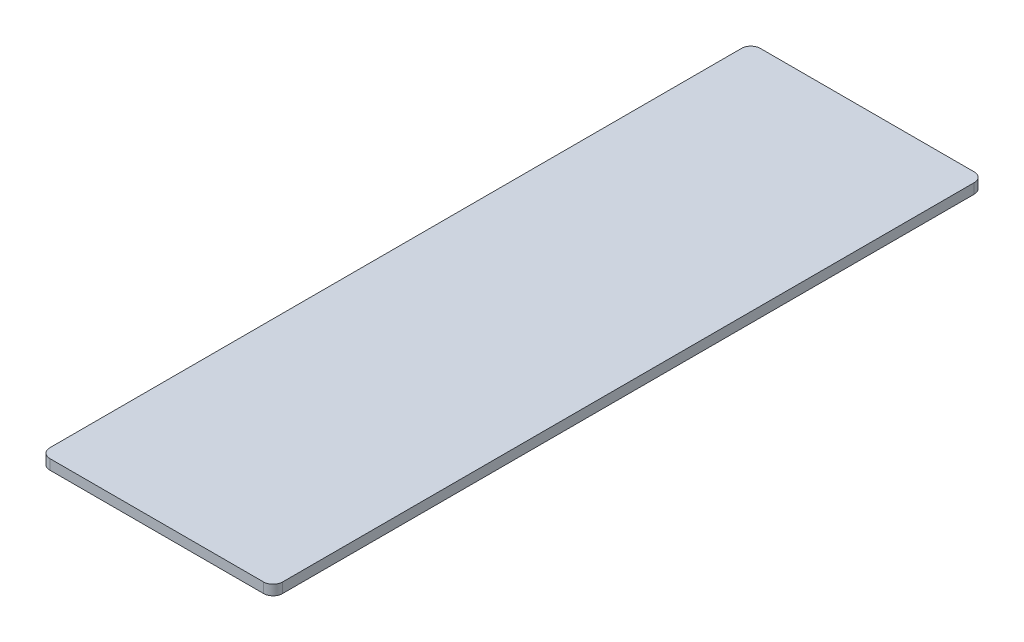
SolidWorks part; units mm, degrees
ref_plane "前视基准面" through (0, 0, 0) normal (0, 0, 1) x (1, 0, 0)
ref_plane "上视基准面" through (0, 0, 0) normal (0, 1, 0) x (1, 0, 0)
ref_plane "右视基准面" through (0, 0, 0) normal (1, 0, 0) x (0, 0, -1)
other "Configuration Table"
sketch "草图1" plane through (0, 0, 0) normal (0, 1, 0) x (1, 0, 0)
  line L0 (25.2806, 0) -> (62.2806, 0)
  line L1 (62.2806, 0) -> (62.2806, -113)
  line L2 (62.2806, -113) -> (25.2806, -113)
  line L3 (25.2806, -113) -> (25.2806, 0)
extrude "凸台-拉伸1" add sketch "草图1" along normal blind 1.6
fillet "圆角1" radius 1.5 4 edges at (62.2806, 0.8, 0) (62.2806, 0.8, 113) (25.2806, 0.8, 0) (25.2806, 0.8, 113)
